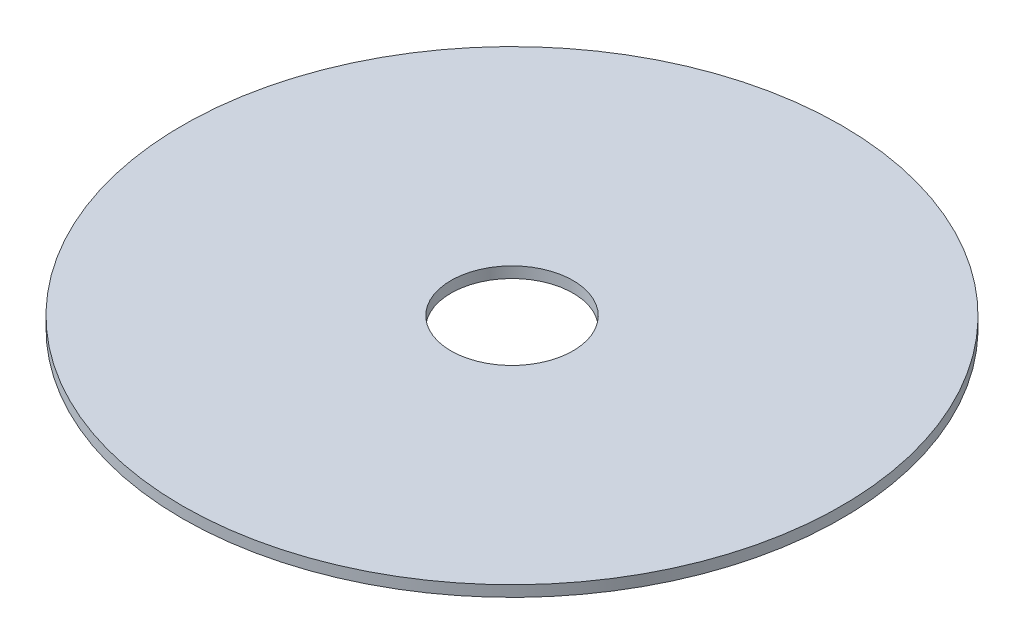
SolidWorks part; units mm, degrees
ref_plane "Alzado" through (0, 0, 0) normal (0, 0, 1) x (1, 0, 0)
ref_plane "Planta" through (0, 0, 0) normal (0, 1, 0) x (1, 0, 0)
ref_plane "Vista lateral" through (0, 0, 0) normal (1, 0, 0) x (0, 0, -1)
sketch "Croquis1" plane through (0, 0, 0) normal (0, 1, 0) x (1, 0, 0)
  circle A0 centre (0, 0) radius 60
  circle A1 centre (0, 0) radius 11.11
  dimension "D1" = 120
  dimension "D2" = 22.22
extrude "Saliente-Extruir1" add sketch "Croquis1" along normal blind 2
